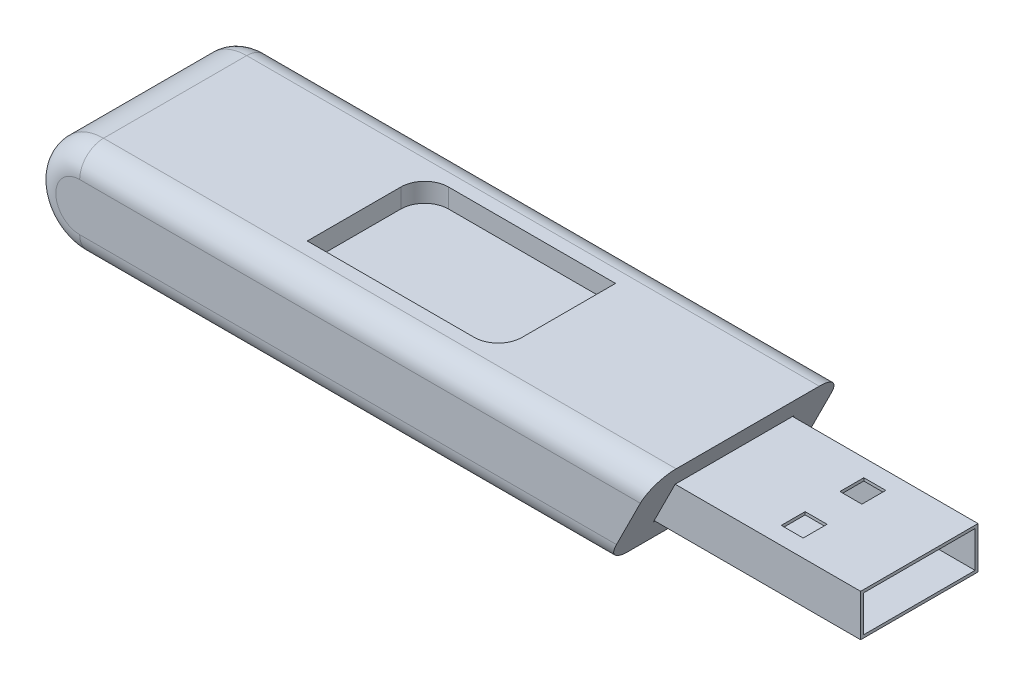
SolidWorks part; units mm, degrees
ref_plane "Front Plane" through (0, 0, 0) normal (0, 0, 1) x (1, 0, 0)
ref_plane "Top Plane" through (0, 0, 0) normal (0, 1, 0) x (1, 0, 0)
ref_plane "Right Plane" through (0, 0, 0) normal (1, 0, 0) x (0, 0, -1)
sketch "Sketch1" plane through (0, 0, 0) normal (0, 0, 1) x (1, 0, 0)
  line L1 (-27.9829, 10) -> (32.0171, 10)
  line L2 (-27.9829, 0) -> (27.0171, 0)
  line L3 (27.0171, 0) -> (32.0171, 10)
  arc A0 (-27.9829, 0) -> (-27.9829, 10) centre (-27.9829, 5) cw
  point P0 (-28.0194, 9.7211)
  dimension "D3" = 5
  dimension "D1" = 60
  dimension "D2" = 55
extrude "Boss-Extrude1" add sketch "Sketch1" along normal blind 20
ref_plane "Plane1" through (50, 0, 0) normal (1, 0, 0) x (0, 0, -1)
sketch "Sketch2" plane through (50, 0, 0) normal (1, 0, 0) x (0, 0, -1)
  line L0 (-10, 10) -> (-10, 0) construction
  line L1 (-16.25, 7.3) -> (-3.75, 7.3)
  line L2 (-16.25, 7.3) -> (-16.25, 2.7)
  line L3 (-16.25, 2.7) -> (-3.75, 2.7)
  line L4 (-3.75, 7.3) -> (-3.75, 2.7)
  line L5 (-20, 10) -> (0, 10) construction
  line L6 (-20, 0) -> (0, 0) construction
  line L7 (-20, 5) -> (0, 5) construction
  line L8 (-20, 0) -> (-20, 10) construction
  line L9 (0, 0) -> (0, 10) construction
  dimension "D1" = 12.5
  dimension "D2" = 4.6
extrude "Cut-Extrude1" cut sketch "Sketch2" against normal blind 60
sketch "Sketch4" plane through (50, 0, 0) normal (1, 0, 0) x (0, 0, -1)
  line L4 (-4.15, 6.9) -> (-15.85, 6.9)
  line L5 (-15.85, 6.9) -> (-15.85, 3.1)
  line L6 (-15.85, 3.1) -> (-4.15, 3.1)
  line L7 (-4.15, 3.1) -> (-4.15, 6.9)
  line L8 (-16.15, 7.2) -> (-16.15, 2.8)
  line L9 (-16.15, 2.8) -> (-3.85, 2.8)
  line L10 (-3.85, 2.8) -> (-3.85, 7.2)
  line L11 (-3.85, 7.2) -> (-16.15, 7.2)
  line L12 (-16.15, 7.2) -> (-16.15, 2.8)
  line L13 (-16.15, 2.8) -> (-3.85, 2.8)
  line L14 (-3.85, 2.8) -> (-3.85, 7.2)
  line L15 (-3.85, 7.2) -> (-16.15, 7.2)
  dimension "D1" = 0.1
  dimension "D2" = 0.3
extrude "Boss-Extrude3" add sketch "Sketch4" against normal blind 40 separate body
sketch "Sketch5" plane through (-10, 0, 0) normal (1, 0, 0) x (0, 0, -1)
  line L0 (-15.85, 6.9) -> (-15.85, 3.1) construction
  line L1 (-15.75, 5.1) -> (-4.25, 5.1)
  line L2 (-15.85, 5.1) -> (-15.85, 3.2783)
  line L3 (-15.85, 3.1) -> (-4.15, 3.1)
  line L4 (-4.15, 5.1) -> (-4.15, 3.1)
  line L5 (-15.75, 5.1) -> (-15.75, 3.2)
  line L6 (-4.25, 5.1) -> (-4.25, 3.2)
  line L7 (-4.25, 3.2) -> (-15.75, 3.2)
  dimension "D1" = 2
  dimension "D2" = 0.1
  dimension "D3" = 0.1
  dimension "D4" = 0.1
sketch "Sketch6" plane through (0, 7.2, 0) normal (0, 1, 0) x (1, 0, 0)
  line L0 (32.0171, -10) -> (50, -10) construction
  line L1 (39.8586, -5.675) -> (42.1586, -5.675)
  line L2 (39.8586, -5.675) -> (39.8586, -8.175)
  line L3 (39.8586, -8.175) -> (42.1586, -8.175)
  line L4 (42.1586, -5.675) -> (42.1586, -8.175)
  line L5 (32.0171, -20) -> (32.0171, 0) construction
  line L6 (50, -5.5) -> (50, 5.5) construction
  line L7 (41.0086, -10) -> (41.0086, -3.85) construction
  line L8 (10, -3.85) -> (50, -3.85) construction
  line L9 (42.1586, -14.325) -> (42.1586, -11.825)
  line L10 (39.8586, -11.825) -> (42.1586, -11.825)
  line L11 (39.8586, -14.325) -> (39.8586, -11.825)
  line L12 (39.8586, -14.325) -> (42.1586, -14.325)
  line L13 (41.0086, -6.925) -> (32.0171, -6.925) construction
  line L14 (32.0171, -6.925) -> (50, -6.925) construction
  line L15 (41.0086, -10) -> (41.0086, -16.15) construction
  line L16 (10, -16.15) -> (50, -16.15) construction
  line L17 (41.0086, -16.15) -> (41.0086, -13.075) construction
  line L18 (41.0086, -13.075) -> (32.0171, -13.075) construction
  line L19 (32.0171, -13.075) -> (50, -13.075) construction
  point P27 (0, 0)
  dimension "D1" = 2.5
  dimension "D2" = 2.3
extrude "Cut-Extrude8" cut sketch "Sketch6" against normal up to next (0.3 mm away)
sketch "Sketch7" plane through (0, 10, 0) normal (0, 1, 0) x (1, 0, 0)
  line L0 (32.9933, -3.85) -> (-27.9829, -3.85) construction
  line L1 (-5.4829, -3.85) -> (12.0171, -3.85)
  line L2 (-7.9829, -6.35) -> (-7.9829, -16.15)
  line L3 (-7.9829, -16.15) -> (9.5171, -16.15)
  line L4 (12.0171, -3.85) -> (12.0171, -13.65)
  line L5 (10, -3.85) -> (50, -3.85) construction
  line L6 (-27.9829, -20) -> (-27.9829, 0) construction
  line L7 (10, -16.15) -> (50, -16.15) construction
  line L8 (32.9933, -16.15) -> (-27.9829, -16.15) construction
  arc A0 (9.5171, -16.15) -> (12.0171, -13.65) centre (9.5171, -13.65) ccw
  arc A1 (-7.9829, -6.35) -> (-5.4829, -3.85) centre (-5.4829, -6.35) cw
  point P18 (-7.9829, -3.85)
  dimension "D3" = 2.5
  dimension "D1" = 20
  dimension "D2" = 20
extrude "Cut-Extrude10" cut sketch "Sketch7" against normal blind 2
fillet "Fillet1" radius 2.5 3 edges at (2.0171, 10, 20) (-0.4829, 0, 20) (-32.9829, 5, 20)
fillet "Fillet2" radius 2.5 3 edges at (-0.4829, 0, 0) (-32.9829, 5, 0) (2.0171, 10, 0)
